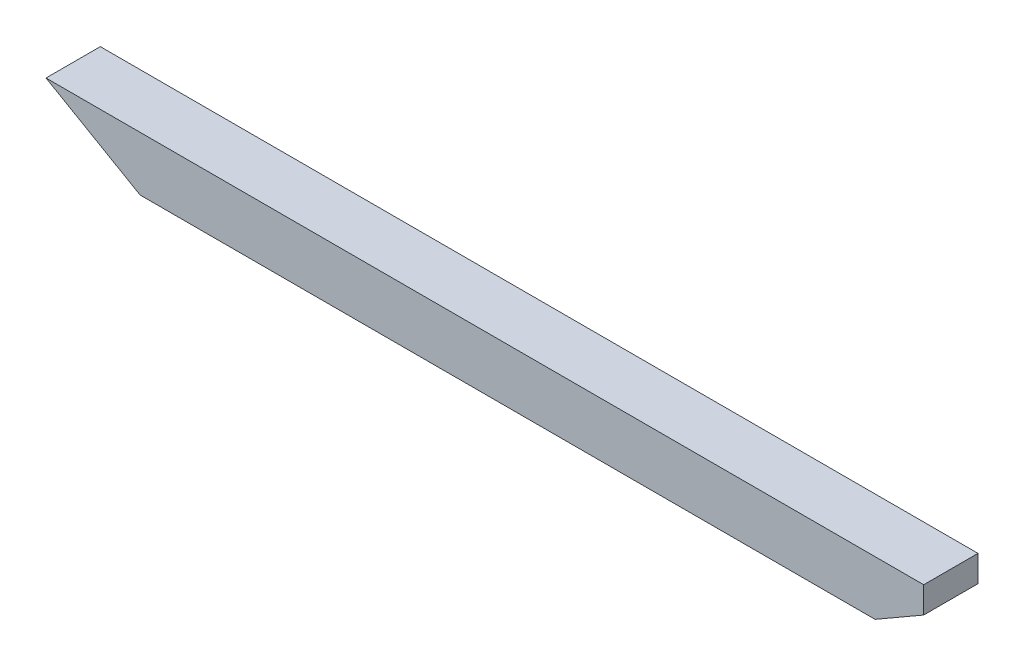
SolidWorks part; units mm, degrees
ref_plane "Front Plane" through (0, 0, 0) normal (0, 0, 1) x (1, 0, 0)
ref_plane "Top Plane" through (0, 0, 0) normal (0, 1, 0) x (1, 0, 0)
ref_plane "Right Plane" through (0, 0, 0) normal (1, 0, 0) x (0, 0, -1)
sketch "Sketch1" plane through (0, 0, 0) normal (0, 0, 1) x (1, 0, 0)
  line L0 (-183.5987, 34.3843) -> (121.6654, 34.3843)
  line L1 (121.6654, 14.3843) -> (-148.9546, 14.3843)
  line L2 (-148.9546, 14.3843) -> (-183.5987, 34.3843)
  line L4 (121.6654, 14.3843) -> (139.5654, 24.7143)
  line L5 (121.6654, 34.3843) -> (139.5654, 34.3843)
  line L6 (139.5654, 34.3843) -> (139.5654, 24.7143)
  point P2 (121.6654, 34.3843)
  point P5 (139.5654, 24.0543)
  dimension "D1" = 20
  dimension "D5" = 40.0027
  dimension "D6" = 17.9
extrude "Boss-Extrude2" add sketch "Sketch1" along normal blind 20
